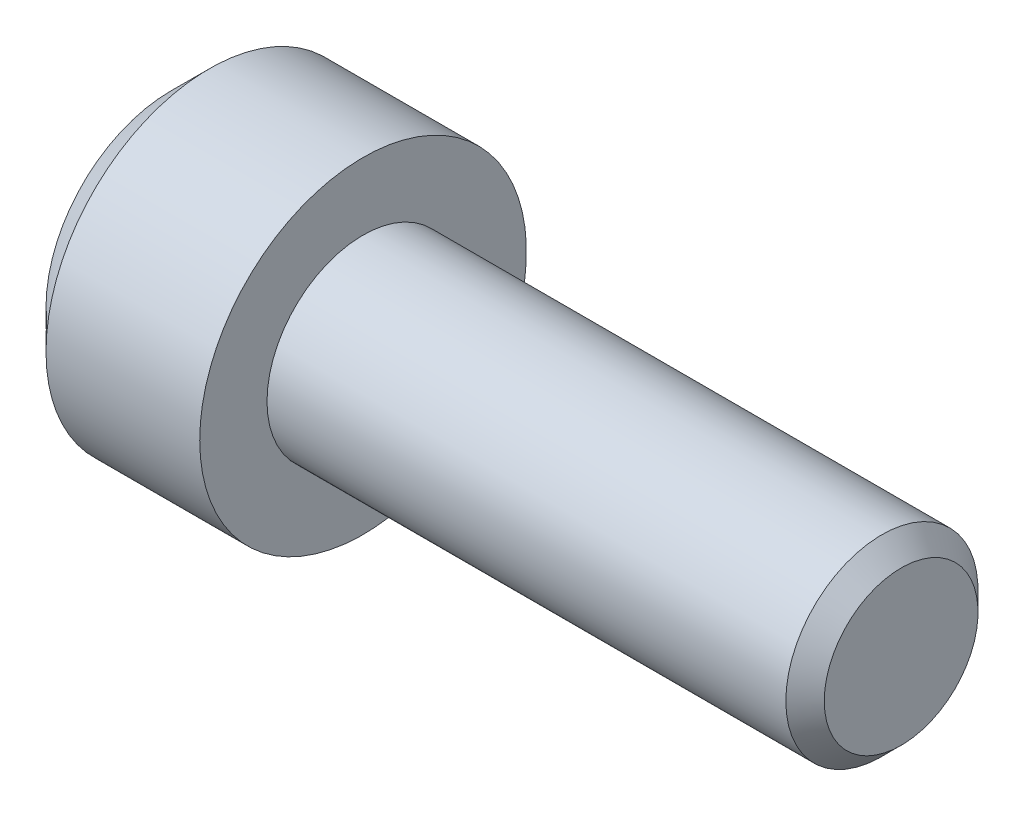
SolidWorks part; units mm, degrees
ref_plane "前视基准面" through (0, 0, 0) normal (0, 0, 1) x (1, 0, 0)
ref_plane "上视基准面" through (0, 0, 0) normal (0, 1, 0) x (1, 0, 0)
ref_plane "右视基准面" through (0, 0, 0) normal (1, 0, 0) x (0, 0, -1)
sketch "草图1" plane through (0, 0, 0) normal (0, 0, 1) x (1, 0, 0)
  line L0 (0, 0) -> (0, 2.5)
  line L1 (0, 2.5) -> (-14, 2.5)
  line L2 (-14, 2.5) -> (-14, 4.25)
  line L3 (-14, 4.25) -> (-19, 4.25)
  line L4 (-19, 4.25) -> (-19, 0)
  line L5 (-19, 0) -> (0, 0)
  line L6 (0, 0) -> (4.7488, 0) construction
  dimension "D1" = 5
  dimension "D2" = 14
  dimension "D3" = 5
  dimension "D4" = 8.5
revolve "旋转1" add sketch "草图1" angle 360 about L6
cosmetic thread "装饰螺纹线1" parameters "D1"=3, "D2"=1.72
chamfer "倒角1" distance 0.5 angle 45 1 edges at (0, 0, 2.5)
sketch "草图2" plane through (-19, 0, 0) normal (-1, 0, 0) x (0, 0, 1)
  line L1 (0, 2.3094) -> (-2, 1.1547)
  line L2 (-2, 1.1547) -> (-2, -1.1547)
  line L3 (-2, -1.1547) -> (0, -2.3094)
  line L4 (0, -2.3094) -> (2, -1.1547)
  line L5 (2, -1.1547) -> (2, 1.1547)
  line L6 (2, 1.1547) -> (0, 2.3094)
  circle A0 centre (0, 0) radius 2 construction
  dimension "D1" = 4
extrude "切除-拉伸1" cut sketch "草图2" against normal blind 2.5
chamfer "倒角2" distance 1 angle 45 1 edges at (-19, 0, 4.25)
sketch "草图4" plane through (-16.5, 0, 0) normal (-1, 0, 0) x (0, 0, 1)
  line L1 (0, -2.3094) -> (2, -1.1547)
  line L2 (2, -1.1547) -> (2, 1.1547)
  line L3 (2, 1.1547) -> (0, 2.3094)
  line L4 (0, 2.3094) -> (-2, 1.1547)
  line L5 (-2, 1.1547) -> (-2, -1.1547)
  line L6 (2, 1.1547) -> (0, 2.3094)
  line L7 (0, 2.3094) -> (-2, 1.1547)
  line L8 (-2, 1.1547) -> (-2, -1.1547)
  line L9 (-2, -1.1547) -> (0, -2.3094)
  line L10 (0, -2.3094) -> (2, -1.1547)
  line L11 (2, -1.1547) -> (2, 1.1547)
  line L12 (2, 1.1547) -> (0, 2.3094) construction
  line L13 (0, 2.3094) -> (-2, 1.1547) construction
  line L14 (-2, 1.1547) -> (-2, -1.1547) construction
  line L15 (-2, -1.1547) -> (0, -2.3094) construction
  line L16 (0, -2.3094) -> (2, -1.1547) construction
  line L17 (2, -1.1547) -> (2, 1.1547) construction
  line L18 (-2, -1.1547) -> (0, -2.3094)
  circle A0 centre (0, 0) radius 2 construction
  dimension "D1" = 0
extrude "切除-拉伸2" cut sketch "草图4" against normal through all draft 59
